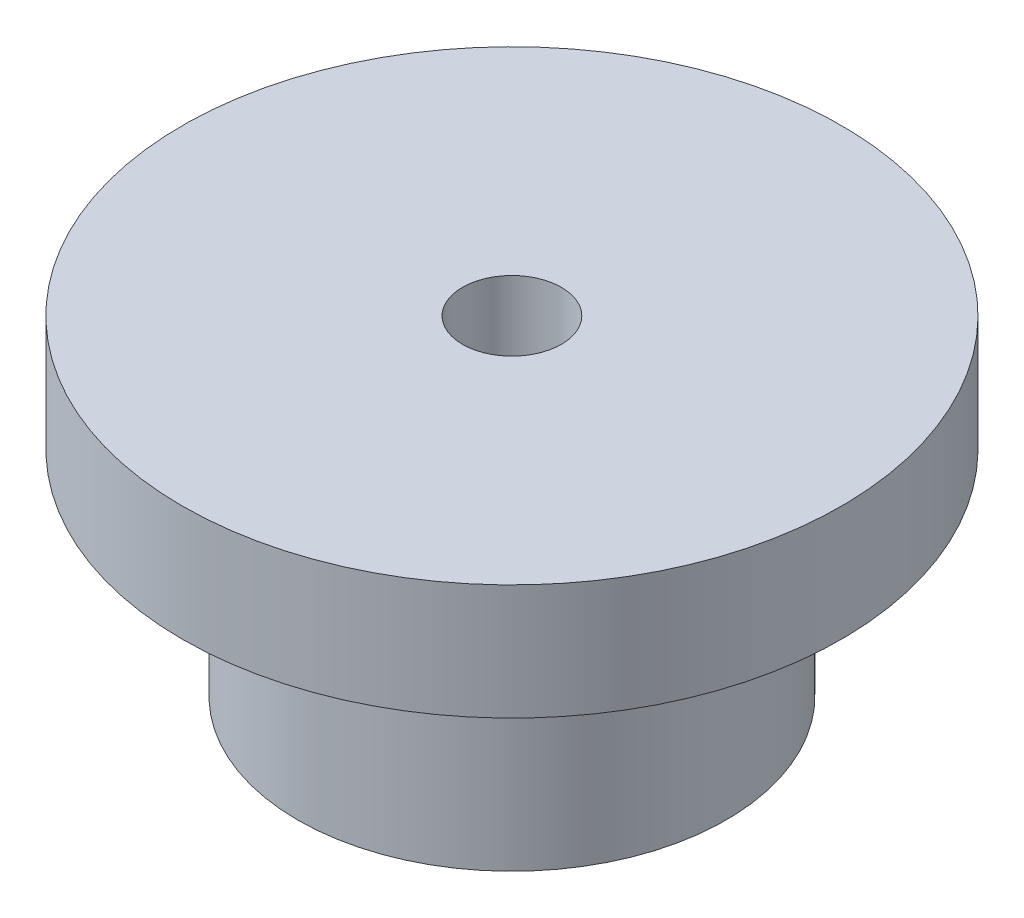
SolidWorks part; units mm, degrees
ref_plane "Спереди" through (0, 0, 0) normal (0, 0, 1) x (1, 0, 0)
ref_plane "Сверху" through (0, 0, 0) normal (0, 1, 0) x (1, 0, 0)
ref_plane "Справа" through (0, 0, 0) normal (1, 0, 0) x (0, 0, -1)
sketch "Эскиз1" plane through (0, 0, 0) normal (0, 1, 0) x (1, 0, 0)
  circle A0 centre (0, 0) radius 13
extrude "Вытянуть1" add sketch "Эскиз1" along normal blind 20
sketch "Эскиз2" plane through (0, 0, 0) normal (0, -1, 0) x (1, 0, 0)
  circle A0 centre (0, 0) radius 5.5
extrude "Вытянуть2" cut sketch "Эскиз2" against normal blind 5
sketch "Эскиз3" plane through (0, 5, 0) normal (0, -1, 0) x (1, 0, 0)
  circle A0 centre (0, 0) radius 5
extrude "Вытянуть3" cut sketch "Эскиз3" against normal blind 10 draft 7
sketch "Эскиз5" plane through (0, 20, 0) normal (0, 1, 0) x (-1, 0, 0)
  circle A0 centre (0, 0) radius 20
extrude "Вытянуть7" add sketch "Эскиз5" against normal blind 7
sketch "Эскиз7" plane through (0, 20, 0) normal (0, 1, 0) x (1, 0, 0)
  circle A0 centre (0, 0) radius 3
extrude "Вытянуть8" cut sketch "Эскиз7" against normal through all
